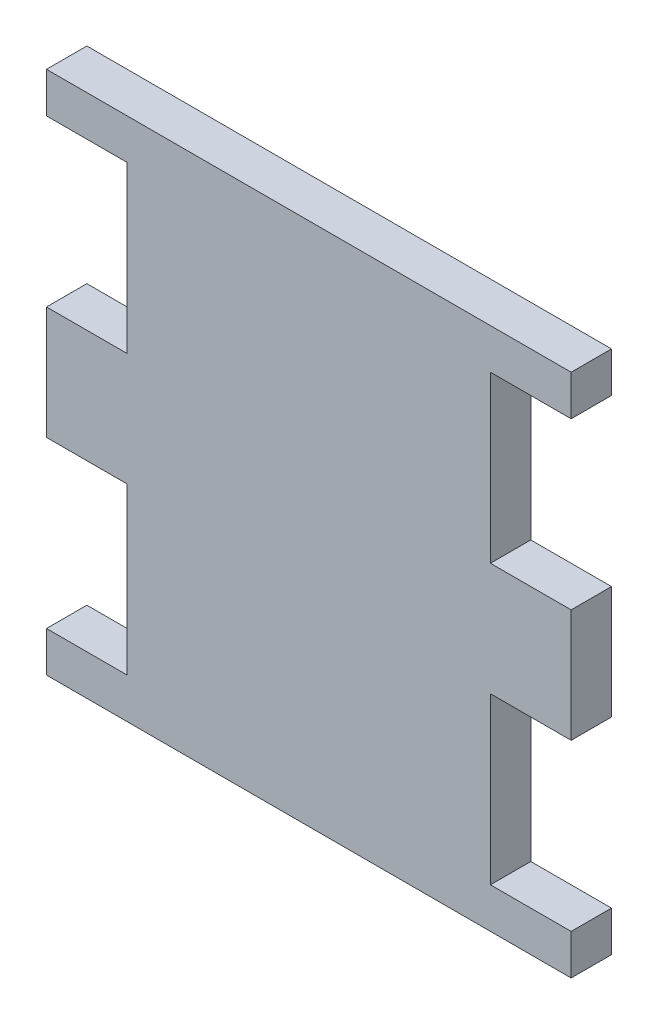
SolidWorks part; units mm, degrees
ref_plane "Plan de face" through (0, 0, 0) normal (0, 0, 1) x (1, 0, 0)
ref_plane "Plan de dessus" through (0, 0, 0) normal (0, 1, 0) x (1, 0, 0)
ref_plane "Plan de droite" through (0, 0, 0) normal (1, 0, 0) x (0, 0, -1)
sketch "Esquisse1" plane through (0, 0, 0) normal (0, 0, 1) x (1, 0, 0)
  line L1 (0, 0) -> (130, 0)
  line L2 (0, 0) -> (0, -130)
  line L3 (0, -130) -> (130, -130)
  line L4 (130, 0) -> (130, -130)
  dimension "D1" = 130
  dimension "D2" = 130
extrude "Boss.-Extru.1" add sketch "Esquisse1" along normal blind 10
sketch "Esquisse2" plane through (0, 0, 10) normal (0, 0, 1) x (1, 0, 0)
  line L0 (0, 0) -> (0, -130) construction
  line L1 (0, -10) -> (20, -10)
  line L2 (0, -10) -> (0, -51)
  line L3 (0, -51) -> (20, -51)
  line L4 (20, -10) -> (20, -51)
  line L5 (130, 0) -> (0, 0) construction
  line L6 (0, -130) -> (130, -130) construction
  line L7 (0, -120) -> (20, -120)
  line L8 (0, -120) -> (0, -79)
  line L9 (0, -79) -> (20, -79)
  line L10 (20, -120) -> (20, -79)
  line L11 (130, -130) -> (130, 0) construction
  line L12 (130, -10) -> (110, -10)
  line L13 (130, -10) -> (130, -51)
  line L14 (130, -51) -> (110, -51)
  line L15 (110, -10) -> (110, -51)
  line L17 (130, -79) -> (110, -79)
  line L18 (130, -79) -> (130, -120)
  line L19 (130, -120) -> (110, -120)
  line L20 (110, -79) -> (110, -120)
  dimension "D1" = 10
  dimension "D2" = 41
  dimension "D3" = 20
  dimension "D4" = 41
  dimension "D5" = 10
  dimension "D6" = 20
  dimension "D7" = 20
  dimension "D8" = 10
  dimension "D9" = 41
extrude "Enlèv. mat.-Extru.1" cut sketch "Esquisse2" against normal blind 10
